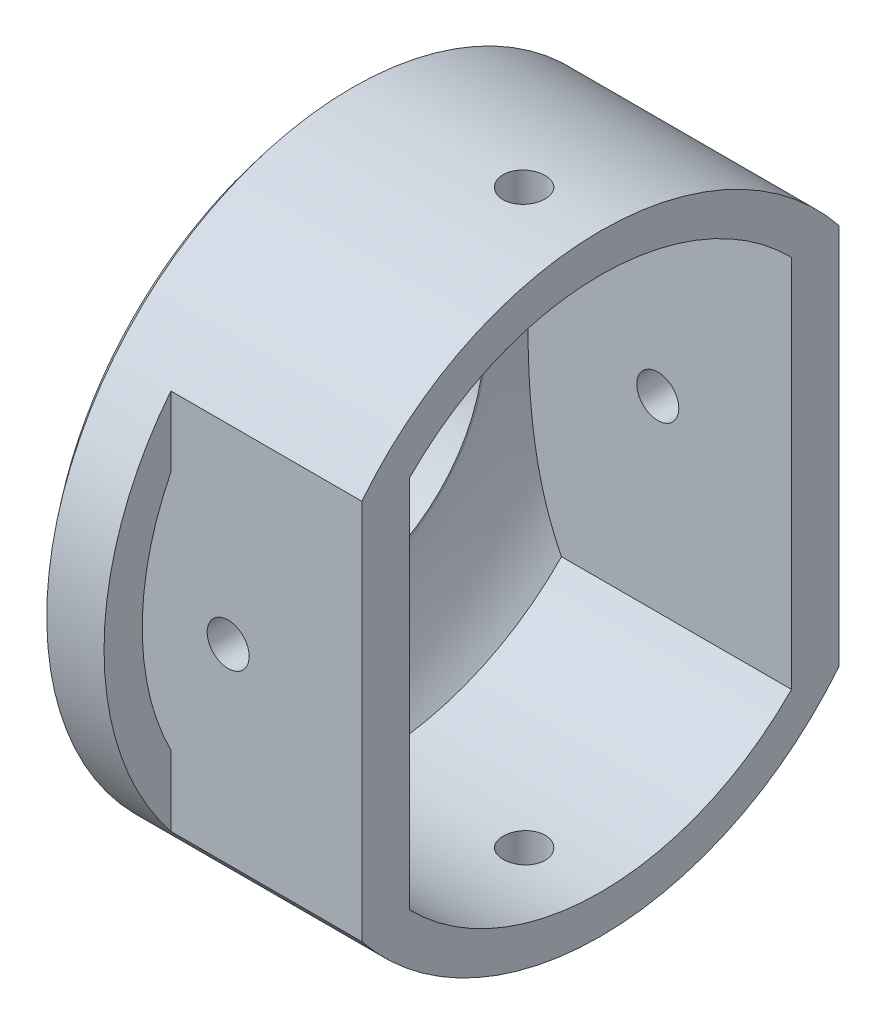
SolidWorks part; units mm, degrees
ref_plane "Front" through (0, 0, 0) normal (0, 0, 1) x (1, 0, 0)
ref_plane "Top" through (0, 0, 0) normal (0, 1, 0) x (1, 0, 0)
ref_plane "Right" through (0, 0, 0) normal (1, 0, 0) x (0, 0, -1)
sketch "Sketch1" plane through (0, 0, 0) normal (0, 0, 1) x (1, 0, 0)
  line L0 (0, 0) -> (0, 16)
  line L1 (0, 0) -> (-6, 0)
  line L2 (-6, 0) -> (-6, 8)
  line L3 (0, 16) -> (-3, 16)
  arc A1 (-3, 16) -> (-6, 8) centre (6.1667, 8) ccw
  point P8 (0, 0)
  dimension "D2" = 8
  dimension "D3" = 6
  dimension "D1" = 16
  dimension "D4" = 3
revolve "Revolve1" add sketch "Sketch1" angle 360 about L1
shell "Shell1" thickness 2
sketch "Sketch2" plane through (-4, 0, 0) normal (1, 0, 0) x (0, 0, -1)
  circle A0 centre (0, 0) radius 7.9
  point P3 (0.7855, -3.0668)
  point P4 (0, 0)
  dimension "D1" = 15.8
extrude "Cut-Extrude1" cut sketch "Sketch2" against normal up to next
sketch "Sketch3" plane through (0, 0, 0) normal (1, 0, 0) x (0, 0, -1)
  line L1 (-10, 9.9875) -> (-12.5, 9.9875)
  line L2 (-10, 9.9875) -> (-10, -9.9875)
  line L3 (-10, -9.9875) -> (-12.5, -9.9875)
  line L4 (-12.5, 9.9875) -> (-12.5, -9.9875)
  line L5 (-10, 9.9875) -> (-12.5, -9.9875) construction
  line L6 (-10, -9.9875) -> (-12.5, 9.9875) construction
  line L7 (10, 9.9875) -> (12.5, 9.9875)
  line L8 (10, 9.9875) -> (10, -9.9875)
  line L9 (10, -9.9875) -> (12.5, -9.9875)
  line L10 (12.5, 9.9875) -> (12.5, -9.9875)
  line L11 (10, 9.9875) -> (12.5, -9.9875) construction
  line L12 (10, -9.9875) -> (12.5, 9.9875) construction
  circle A1 centre (0, 0) radius 16 construction
  point P4 (-11.25, 0)
  point P5 (12.5, 9.9875)
  point P6 (12.5, -9.9875)
  point P7 (9.7289, -12.7023)
  point P8 (10, 12.49)
  point P9 (10, -12.49)
  point P14 (11.25, 0)
  point P15 (-12.5, 9.9875)
  point P19 (-12.5, -9.9875)
  circle M11 centre (0, 0) radius 14
  dimension "D1" = 10
  dimension "D2" = 2.5
  dimension "D3" = 10
  dimension "D4" = 2.5
extrude "Boss-Extrude1" add sketch "Sketch3" along normal blind 10 and the other way up to surface contours L4 L2 M11 | L10 L8 M11 | L1 L4 L2 M11 | L4 L3 L2 M11 | L10 L8 L9 M11 | L10 L7 L8 M11 other way up to face at (-4, 8, 0)
sketch "Sketch4" plane through (0, 0, 12.5) normal (0, 0, 1) x (1, 0, 0)
  line L1 (-6, 8) -> (-6, -8) construction
  circle A0 centre (3, 0) radius 1.1
  dimension "D1" = 2.2
  dimension "D2" = 9
extrude "Cut-Extrude2" cut sketch "Sketch4" against normal through all
sketch "Sketch5" plane through (0, 0, 0) normal (1, 0, 0) x (0, 0, -1)
  line L20 (10, 9.798) -> (10, 9.9875)
  line L21 (10, 9.9875) -> (12.5, 9.9875)
  line L22 (-12.5, 9.9875) -> (-10, 9.9875)
  line L23 (-10, 9.9875) -> (-10, 9.798)
  line L24 (10, 9.798) -> (10, 9.9875)
  line L25 (10, 9.9875) -> (12.5, 9.9875)
  line L26 (-12.5, 9.9875) -> (-10, 9.9875)
  line L27 (-10, 9.9875) -> (-10, 9.798)
  line L28 (12.5, -9.9875) -> (10, -9.9875)
  line L29 (10, -9.9875) -> (10, -9.798)
  line L30 (-10, -9.798) -> (-10, -9.9875)
  line L31 (-10, -9.9875) -> (-12.5, -9.9875)
  line L32 (12.5, -9.9875) -> (10, -9.9875)
  line L33 (10, -9.9875) -> (10, -9.798)
  line L34 (-10, -9.798) -> (-10, -9.9875)
  line L35 (-10, -9.9875) -> (-12.5, -9.9875)
  arc A26 (12.5, 9.9875) -> (-12.5, 9.9875) centre (0, 0) ccw
  arc A27 (10, 9.798) -> (-10, 9.798) centre (0, 0) ccw
  arc A28 (12.5, 9.9875) -> (-12.5, 9.9875) centre (0, 0) ccw
  arc A29 (10, 9.798) -> (-10, 9.798) centre (0, 0) ccw
  arc A30 (-10, -9.798) -> (10, -9.798) centre (0, 0) ccw
  arc A31 (-12.5, -9.9875) -> (12.5, -9.9875) centre (0, 0) ccw
  arc A32 (-10, -9.798) -> (10, -9.798) centre (0, 0) ccw
  arc A33 (-12.5, -9.9875) -> (12.5, -9.9875) centre (0, 0) ccw
  dimension "D1" = 0
  dimension "D2" = 0
extrude "Boss-Extrude3" add sketch "Sketch5" along normal blind 10
sketch "Sketch6" plane through (0, 0, 0) normal (0, 1, 0) x (1, 0, 0)
  line L1 (-6, 8) -> (-6, -8) construction
  circle A0 centre (6, 0) radius 1.1
  point P4 (0, 0)
  point P6 (0, 0)
  dimension "D1" = 2.2
  dimension "D2" = 12
extrude "Cut-Extrude3" cut sketch "Sketch6" against normal mid plane 45 contours A0
